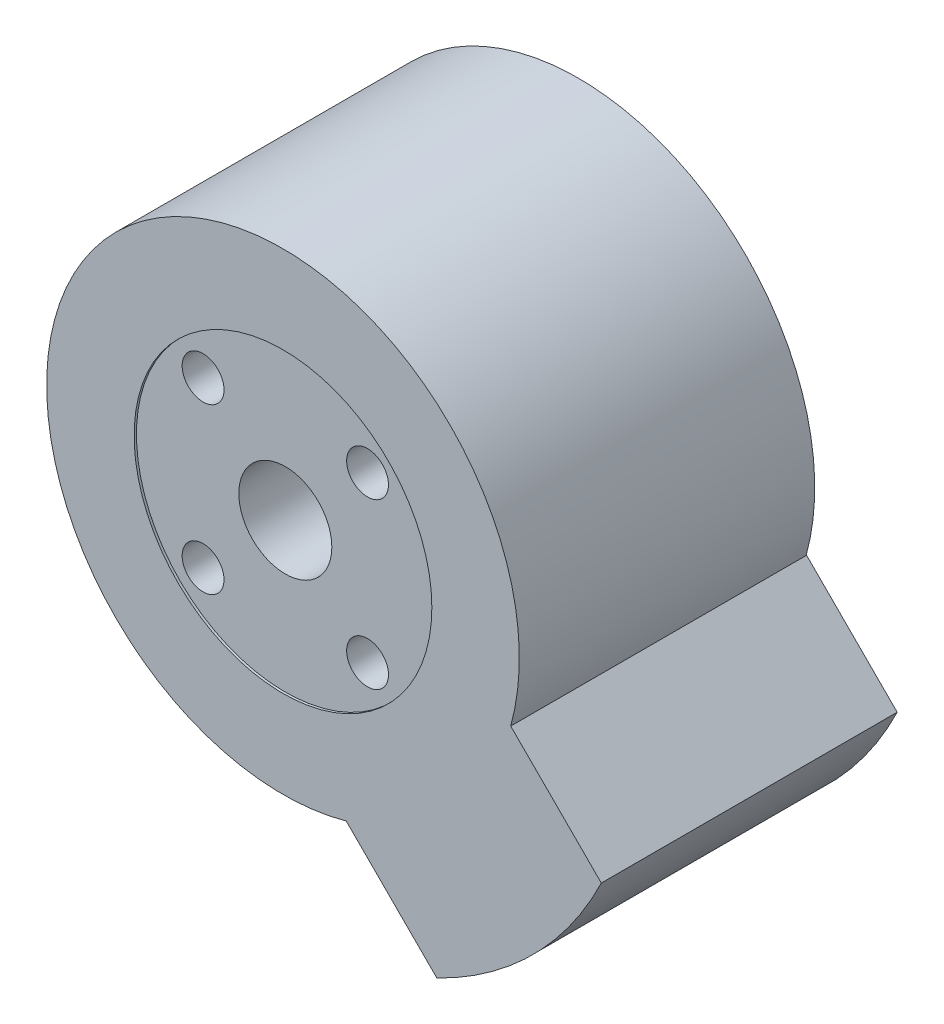
SolidWorks part; units mm, degrees
ref_plane "Front Plane" through (0, 0, 0) normal (0, 0, 1) x (1, 0, 0)
ref_plane "Top Plane" through (0, 0, 0) normal (0, 1, 0) x (1, 0, 0)
ref_plane "Right Plane" through (0, 0, 0) normal (1, 0, 0) x (0, 0, -1)
sketch "Sketch1" plane through (0, 0, 0) normal (0, 0, 1) x (1, 0, 0)
  circle A0 centre (0, 0) radius 25.4
  dimension "D1" = 50.8
extrude "Boss-Extrude1" add sketch "Sketch1" against normal blind 31.75
sketch "Sketch2" plane through (0, 0, 0) normal (0, 0, 1) x (1, 0, 0)
  circle A0 centre (0, 0) radius 16
  dimension "D1" = 32
extrude "Cut-Extrude1" cut sketch "Sketch2" against normal blind 0.25
sketch "Sketch3" plane through (0, 0, -0.25) normal (0, 0, 1) x (1, 0, 0)
  line L1 (-8.8388, 8.8388) -> (8.8388, 8.8388) construction
  line L2 (-8.8388, 8.8388) -> (-8.8388, -8.8388) construction
  line L3 (-8.8388, -8.8388) -> (8.8388, -8.8388) construction
  line L4 (8.8388, 8.8388) -> (8.8388, -8.8388) construction
  line L5 (-8.8388, 8.8388) -> (8.8388, -8.8388) construction
  line L6 (-8.8388, -8.8388) -> (8.8388, 8.8388) construction
  circle A0 centre (0, 0) radius 12.5 construction
  dimension "D1" = 25
hole_wizard "M4 Clearance Hole1" positions "Sketch4" profile "Sketch5" hole size "M4" standard "ANSI Metric" end condition through all
sketch "Sketch4" plane through (0, 0, -0.25) normal (0, 0, 1) x (1, 0, 0)
  point P0 (-8.8388, 8.8388)
  point P3 (8.8388, 8.8388)
  point P6 (-8.8388, -8.8388)
  point P9 (8.8388, -8.8388)
sketch "Sketch5" plane through (-8.8388, 8.8388, -0.25) normal (1, 0, 0) x (0, -1, 0)
  line L0 (0, 0) -> (0, 31.5)
  line L1 (0, 31.5) -> (2.25, 31.5)
  line L2 (2.25, 31.5) -> (2.25, 0)
  line L5 (2.25, 0) -> (0, 0)
  line L11 (0, -6.35) -> (0, 107.95) construction
  dimension "Thru Hole Dia." = 4.5
  dimension "Thru Hole Depth" = 31.5
sketch "Sketch6" plane through (0, 0, -0.25) normal (0, 0, 1) x (1, 0, 0)
  circle A0 centre (0, 0) radius 5
  dimension "D1" = 10
extrude "Cut-Extrude2" cut sketch "Sketch6" against normal through all
sketch "Sketch8" plane through (0, 0, 0) normal (0, 0, 1) x (1, 0, 0)
  line L0 (8.8388, 8.8388) -> (8.8388, -8.8388) construction
  line L1 (26.8701, -26.8701) -> (17.9605, -17.9605) construction
  line L2 (38, 0) -> (25.4, 0) construction
  line L3 (6.7962, -24.4739) -> (16.5359, -34.2135)
  line L4 (24.4739, -6.7962) -> (34.2135, -16.5359)
  arc A0 (16.5359, -34.2135) -> (34.2135, -16.5359) centre (0, 0) ccw
  circle A1 centre (0, 0) radius 25.4 construction
  arc A2 (6.7962, -24.4739) -> (24.4739, -6.7962) centre (0, 0) ccw
  arc A3 (38, 0) -> (16.5359, -34.2135) centre (0, 0) ccw construction
  arc A4 (34.2135, -16.5359) -> (38, 0) centre (0, 0) ccw construction
  arc A5 (25.4, 0) -> (6.7962, -24.4739) centre (0, 0) ccw construction
  arc A6 (24.4739, -6.7962) -> (25.4, 0) centre (0, 0) ccw construction
  point P0 (8.8388, 0)
  point P6 (26.8701, -26.8701)
  point P7 (38, 0)
  dimension "D1" = 76
  dimension "D2" = 45
  dimension "D3" = 25
extrude "Boss-Extrude2" add sketch "Sketch8" against normal blind 31.8
